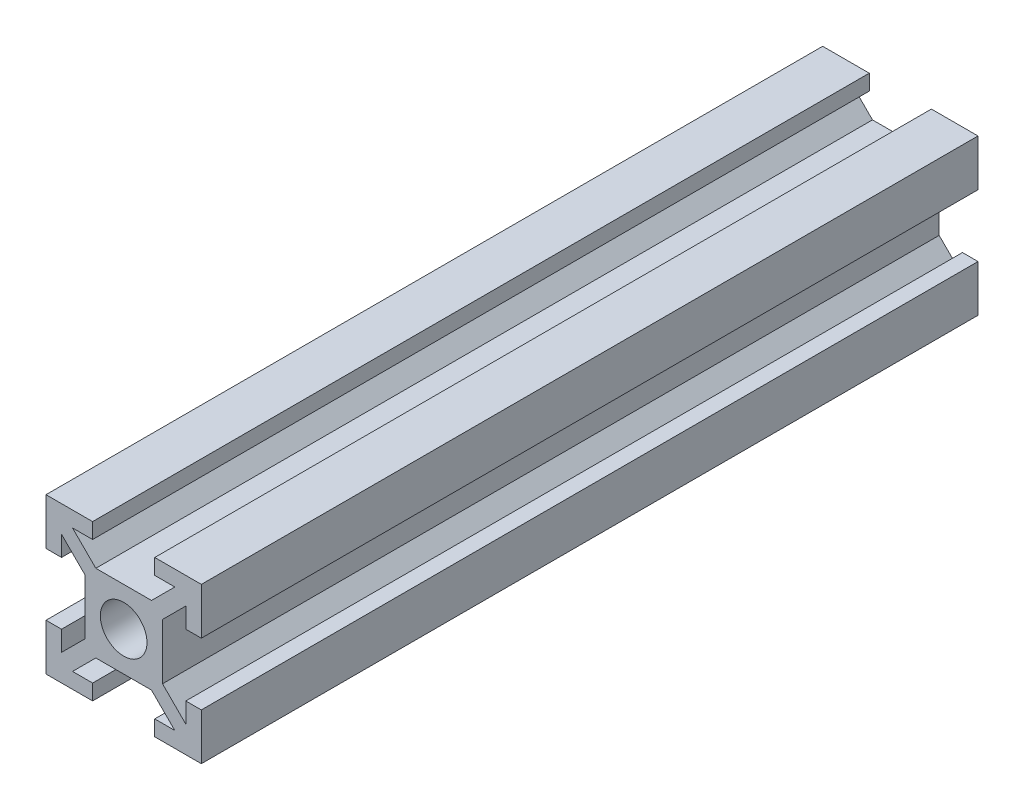
SolidWorks part; units mm, degrees
ref_plane "前视基准面" through (0, 0, 0) normal (0, 0, 1) x (1, 0, 0)
ref_plane "上视基准面" through (0, 0, 0) normal (0, 1, 0) x (1, 0, 0)
ref_plane "右视基准面" through (0, 0, 0) normal (1, 0, 0) x (0, 0, -1)
other "Configuration Table"
sketch "草图1" plane through (0, 0, 0) normal (0, 0, 1) x (1, 0, 0)
  line L0 (-10, 4) -> (-8, 4)
  line L5 (10, 10) -> (-10, 10) construction
  line L6 (10, 10) -> (10, -10) construction
  line L7 (10, -10) -> (-10, -10) construction
  line L8 (-10, 10) -> (-10, -10) construction
  line L9 (10, 10) -> (-10, -10) construction
  line L10 (10, -10) -> (-10, 10) construction
  line L11 (-8, 4) -> (-8, 6.5858)
  line L12 (-8, 6.5858) -> (-5, 3.5858)
  line L13 (-4, 10) -> (-4, 8)
  line L14 (-4, 8) -> (-6.5858, 8)
  line L15 (-6.5858, 8) -> (-3.5858, 5)
  line L16 (-10, 4) -> (-10, 10)
  line L17 (-10, 10) -> (-4, 10)
  line L18 (4, 10) -> (4, 8)
  line L19 (4, 8) -> (6.5858, 8)
  line L20 (6.5858, 8) -> (3.5858, 5)
  line L21 (10, 4) -> (8, 4)
  line L22 (8, 4) -> (8, 6.5858)
  line L23 (8, 6.5858) -> (5, 3.5858)
  line L24 (4, 10) -> (10, 10)
  line L25 (10, 10) -> (10, 4)
  line L26 (10, -4) -> (8, -4)
  line L27 (8, -4) -> (8, -6.5858)
  line L28 (8, -6.5858) -> (5, -3.5858)
  line L29 (4, -10) -> (4, -8)
  line L30 (4, -8) -> (6.5858, -8)
  line L31 (6.5858, -8) -> (3.5858, -5)
  line L32 (10, -4) -> (10, -10)
  line L33 (10, -10) -> (4, -10)
  line L34 (-4, -10) -> (-4, -8)
  line L35 (-4, -8) -> (-6.5858, -8)
  line L36 (-6.5858, -8) -> (-3.5858, -5)
  line L37 (-10, -4) -> (-8, -4)
  line L38 (-8, -4) -> (-8, -6.5858)
  line L39 (-8, -6.5858) -> (-5, -3.5858)
  line L40 (-4, -10) -> (-10, -10)
  line L41 (-10, -10) -> (-10, -4)
  line L43 (-3.5858, 5) -> (3.5858, 5)
  line L44 (-5, 3.5858) -> (-5, -3.5858)
  line L45 (-3.5858, -5) -> (3.5858, -5)
  line L46 (5, 3.5858) -> (5, -3.5858)
  line L47 (-5, 5) -> (5, -5) construction
  line L48 (-5, -5) -> (5, 5) construction
  circle A0 centre (0, 0) radius 3
  point P46 (0, 0)
  dimension "D2" = 6
  dimension "D1" = 20
  dimension "D3" = 2
  dimension "D4" = 2
  dimension "D5" = 6
  dimension "D7" = 10
  dimension "D6" = 4
extrude "凸台-拉伸1" add sketch "草图1" along normal blind 100
